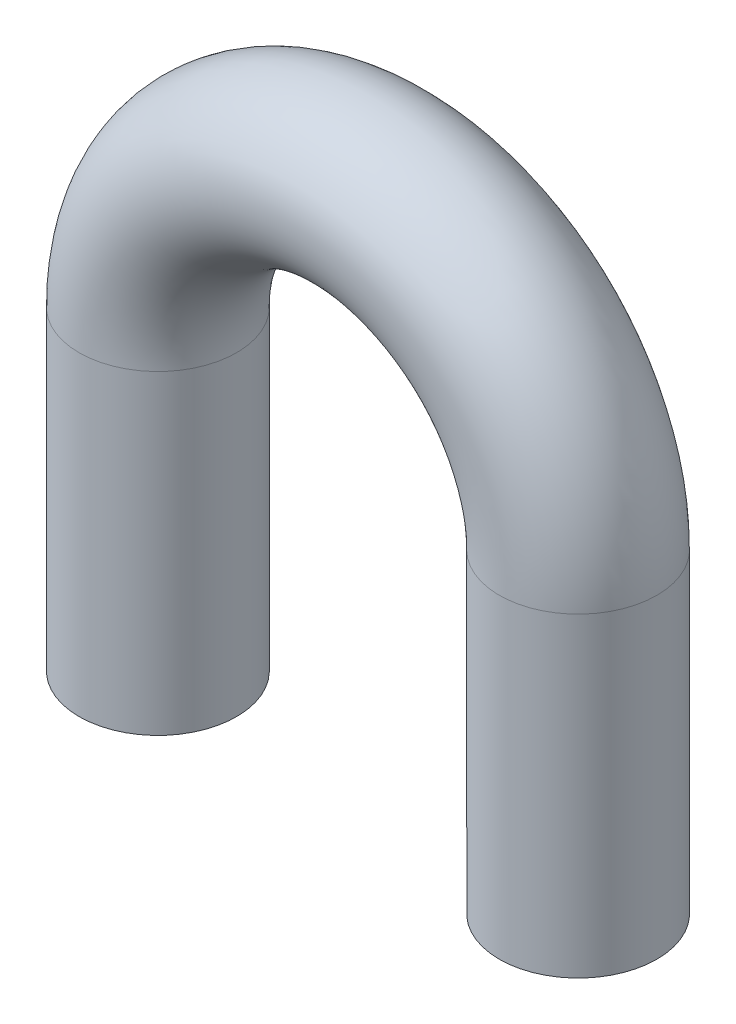
SolidWorks part; units mm, degrees
ref_plane "Front Plane" through (0, 0, 0) normal (0, 0, 1) x (1, 0, 0)
ref_plane "Top Plane" through (0, 0, 0) normal (0, 1, 0) x (1, 0, 0)
ref_plane "Right Plane" through (0, 0, 0) normal (1, 0, 0) x (0, 0, -1)
sketch "Sketch1" plane through (0, 0, 0) normal (0, 0, 1) x (1, 0, 0)
  line L0 (0, 30) -> (0, 0) construction
  line L1 (0, -25.0005) -> (0, 25.0005) construction
  line L2 (20, 30) -> (20, 0) construction
  line L3 (-20, 30) -> (-20, 0) construction
  line L4 (12.6585, 0) -> (-12.6585, 0) construction
  line L5 (-20, 30) -> (-20, 0)
  line L6 (20, 30) -> (20, 0)
  arc A0 (20, 30) -> (-20, 30) centre (0, 30) ccw construction
  arc A1 (-20, 0) -> (20, 0) centre (0, 0) ccw construction
  arc A2 (-20, 30) -> (20, 30) centre (0, 30) cw
  point P5 (0, 15)
  dimension "D1" = 30
  dimension "D2" = 40
sketch "Sketch2" plane through (0, 0, 0) normal (0, 1, 0) x (1, 0, 0)
  line L0 (-20, 0) -> (20, 0) construction
  line L1 (-20, 0) -> (20, 0) construction
  circle A0 centre (-20, 0) radius 7.5
  point P8 (0, 0)
  dimension "D1" = 15
sweep "Sweep1" add profiles "Sketch2" path "Sketch1"
